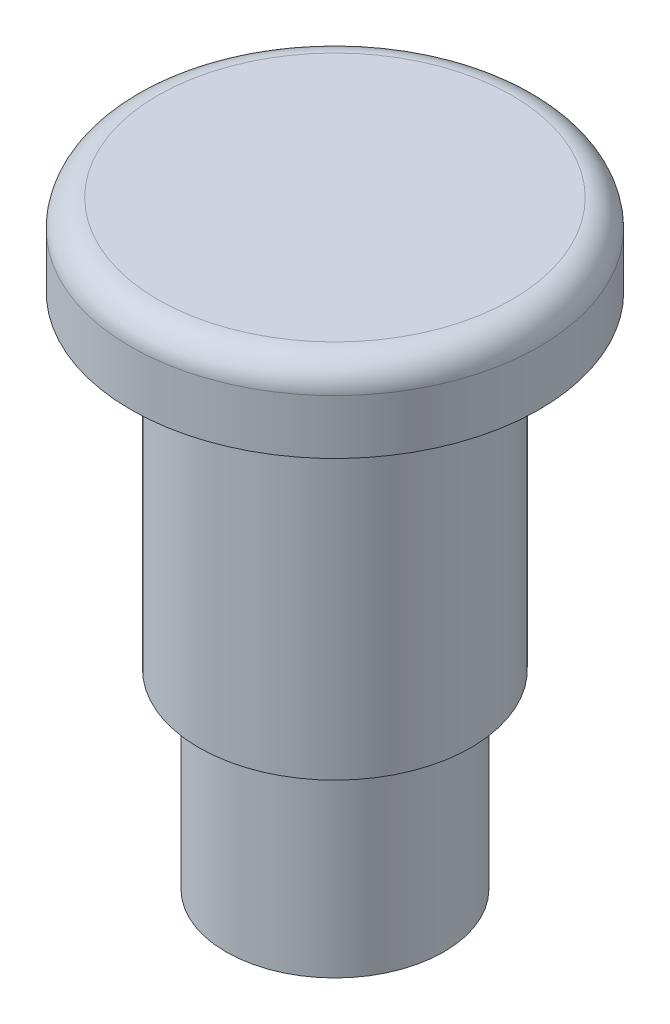
SolidWorks part; units mm, degrees
ref_plane "Front Plane" through (0, 0, 0) normal (0, 0, 1) x (1, 0, 0)
ref_plane "Top Plane" through (0, 0, 0) normal (0, 1, 0) x (1, 0, 0)
ref_plane "Right Plane" through (0, 0, 0) normal (1, 0, 0) x (0, 0, -1)
sketch "Sketch1" plane through (0, 0, 0) normal (0, 0, 1) x (1, 0, 0)
  line L0 (0, 0) -> (-4, 0)
  line L1 (-4, 0) -> (-4, 7)
  line L2 (-4, 7) -> (-5, 7)
  line L3 (-5, 7) -> (-5, 19)
  line L4 (-5, 19) -> (-7.5, 19)
  line L5 (-7.5, 19) -> (-7.5, 21)
  line L6 (-6.5, 22) -> (0, 22)
  line L7 (0, 22) -> (0, 0)
  arc A0 (-7.5, 21) -> (-6.5, 22) centre (-6.5, 21) cw
  point P11 (-7.5, 22)
  dimension "D7" = 1
  dimension "D1" = 7
  dimension "D2" = 12
  dimension "D3" = 3
  dimension "D4" = 4
  dimension "D5" = 5
  dimension "D6" = 7.5
revolve "Revolve1" add sketch "Sketch1" angle 360 about L7
